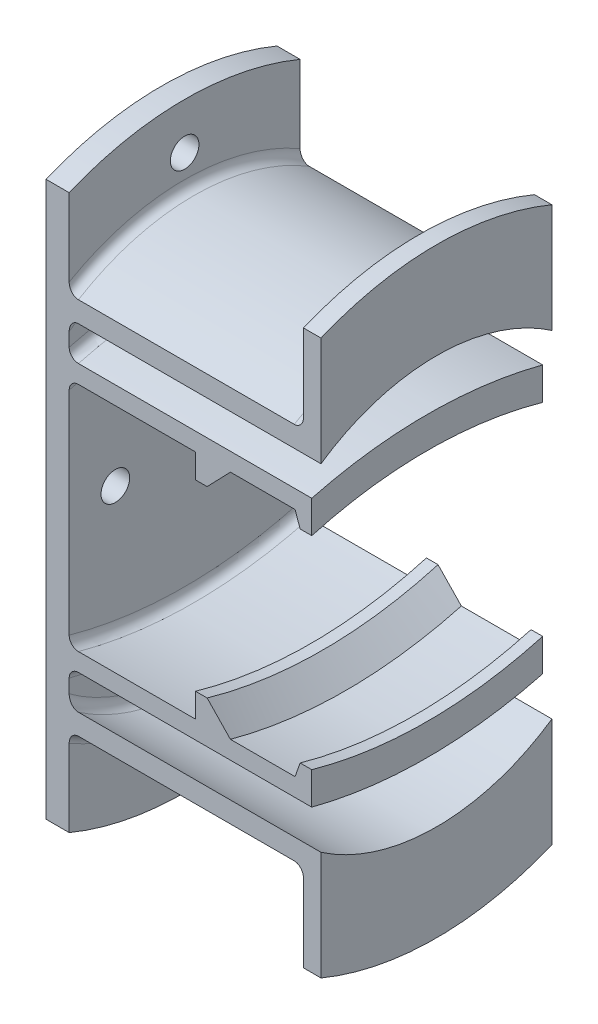
SolidWorks part; units mm, degrees
ref_plane "Front Plane" through (0, 0, 0) normal (0, 0, 1) x (1, 0, 0)
ref_plane "Top Plane" through (0, 0, 0) normal (0, 1, 0) x (1, 0, 0)
ref_plane "Right Plane" through (0, 0, 0) normal (1, 0, 0) x (0, 0, -1)
sketch "Sketch1" plane through (0, 0, 0) normal (0, 0, 1) x (1, 0, 0)
  line L0 (0, 0) -> (0.6934, -1.905)
  line L1 (0.6934, -1.905) -> (2.2934, -1.905)
  line L2 (2.2934, -1.905) -> (2.2934, 2.4)
  line L3 (2.2934, 2.4) -> (-34.2316, 2.4)
  line L4 (0, 0) -> (-8.89, 0)
  line L5 (-13.69, 0) -> (-31.0566, 0)
  line L6 (-31.0566, 0) -> (-31.0566, -60.325)
  line L7 (-31.0566, -60.325) -> (-34.2316, -60.325)
  line L8 (-34.2316, -60.325) -> (-34.2316, 2.4)
  line L9 (-8.89, 0) -> (-12.09, -3.2)
  line L10 (-12.09, -3.2) -> (-13.69, -3.2)
  line L11 (-13.69, -3.2) -> (-13.69, 0)
  dimension "D5" = 135
  dimension "D1" = 8.89
  dimension "D2" = 1.905
  dimension "D3" = 110
  dimension "D4" = 1.6
  dimension "D6" = 2.4
  dimension "D7" = 3.175
  dimension "D8" = 31.75
  dimension "D9" = 60.325
  dimension "D10" = 1.6
  dimension "D11" = 3.2
revolve "Revolve1" add sketch "Sketch1" angle 360 about L7
sketch "Sketch2" plane through (2.2934, 0, 0) normal (1, 0, 0) x (0, 0, -1)
  line L1 (-15.875, 18.034) -> (15.875, 18.034)
  line L2 (-15.875, 18.034) -> (-15.875, -18.034)
  line L3 (-15.875, -18.034) -> (15.875, -18.034)
  line L4 (15.875, 18.034) -> (15.875, -18.034)
  line L5 (-15.875, 18.034) -> (15.875, -18.034) construction
  line L6 (-15.875, -18.034) -> (15.875, 18.034) construction
  point P0 (0, 0)
  dimension "D1" = 31.75
  dimension "D2" = 18.034
extrude "Cut-Extrude1" cut sketch "Sketch2" against normal through all flip side to cut
fillet "Fillet1" radius 1.27 1 edges at (-31.0566, 0, 0)
fillet "Fillet2" radius 2.54 1 edges at (-34.2316, 2.4, 0)
sketch "Sketch5" plane through (0, 0, 0) normal (0, 0, 1) x (1, 0, 0)
  line L0 (-34.2316, -18.034) -> (-31.0566, -18.034) construction
  line L1 (-31.0566, -3.4437) -> (-31.0566, 10.02)
  line L2 (-31.0566, 10.02) -> (3.5634, 10.02)
  line L4 (3.5634, 10.02) -> (3.5634, 23.241)
  line L6 (3.5634, 23.241) -> (1.1634, 23.241)
  line L7 (1.1634, 23.241) -> (1.1634, 12.42)
  line L8 (1.1634, 12.42) -> (-31.0566, 12.42)
  line L9 (-34.2316, 11.15) -> (-34.2316, -3.4437)
  line L10 (2.2934, 2.4) -> (-31.6916, 2.4) construction
  line L11 (-31.0566, -3.4437) -> (-34.2316, -3.4437)
  line L13 (-34.2316, 11.15) -> (-34.2316, 23.241)
  line L14 (-34.2316, 23.241) -> (-31.0566, 23.241)
  line L15 (-31.0566, 23.241) -> (-31.0566, 12.42)
  dimension "D1" = 2.4
  dimension "D2" = 7.62
  dimension "D3" = 41.275
  dimension "D4" = 1.27
  dimension "D5" = 2.4
revolve "RingRevolve2" add sketch "Sketch5" angle 360 about L0
sketch "Sketch6" plane through (2.2934, 0, 0) normal (1, 0, 0) x (0, 0, -1)
  line L0 (-15.875, 0.3579) -> (-15.875, -18.034)
  line L3 (-15.875, -18.034) -> (15.875, -18.034)
  line L4 (15.875, -18.034) -> (15.875, 0.3579)
  line L5 (15.875, 0.3579) -> (15.875, 24.0138)
  line L6 (15.875, 24.0138) -> (-15.875, 24.0138)
  line L7 (-15.875, 24.0138) -> (-15.875, 0.3579)
  line L8 (-14.5903, -18.034) -> (14.5903, -18.034) construction
extrude "RingCut-Extrude3" cut sketch "Sketch6" against normal through all and the other way through all flip side to cut
mirror "Mirror1" about plane through (-34.2316, -18.034, 15.875) normal (0, -1, 0) of bodies 107 103
sketch "Sketch4" plane through (-31.0566, 0, 0) normal (1, 0, 0) x (0, 0, -1)
  line L0 (-15.875, -18.034) -> (-9.525, -18.034) construction
  line L1 (-15.875, -18.034) -> (15.875, -18.034) construction
  line L2 (-9.525, -18.034) -> (9.525, -18.034) construction
  line L3 (9.525, -18.034) -> (15.875, -18.034) construction
  line L4 (15.875, -32.6243) -> (15.875, -3.4437) construction
  circle A0 centre (-9.525, -18.034) radius 1.9685
  circle A1 centre (9.525, -18.034) radius 1.9685
  dimension "D1" = 3.937
  dimension "D2" = 19.05
extrude "Cut-Extrude2" cut sketch "Sketch4" against normal through all
fillet "RingFillet4" radius 1.27 8 edges at (-31.0566, -38.468, 0) (-31.0566, -46.088, 0) (-31.0566, 10.02, 0) (-31.0566, 2.4, 0) (-31.0566, -48.488, 0) (-31.0566, 12.42, 0) (1.1634, -48.488, 0) (1.1634, 12.42, 0)
sketch "Sketch7" plane through (-31.0566, 0, 0) normal (1, 0, 0) x (0, 0, -1)
  line L0 (0, -18.034) -> (0, 16.891) construction
  line L1 (-15.875, -18.034) -> (15.875, -18.034) construction
  line L2 (0, -18.034) -> (0, -52.959) construction
  circle A0 centre (0, 16.891) radius 1.9685
  circle A1 centre (0, -52.959) radius 1.9685
  circle A2 centre (9.525, -18.034) radius 1.9685 construction
  dimension "D1" = 69.85
extrude "Cut-Extrude4" cut sketch "Sketch7" against normal through all
